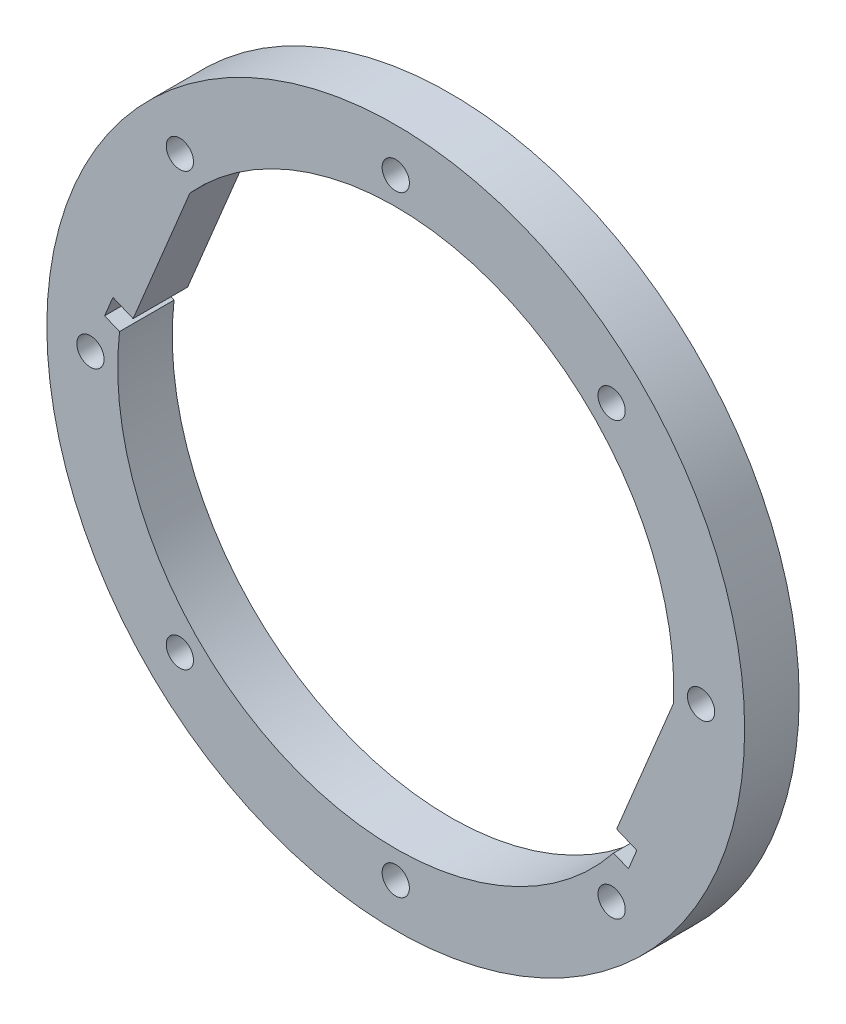
SolidWorks part; units mm, degrees
ref_plane "Alzado" through (0, 0, 0) normal (0, 0, 1) x (1, 0, 0)
ref_plane "Planta" through (0, 0, 0) normal (0, 1, 0) x (1, 0, 0)
ref_plane "Vista lateral" through (0, 0, 0) normal (1, 0, 0) x (0, 0, -1)
sketch "Croquis1" plane through (0, 0, 0) normal (0, 0, 1) x (1, 0, 0)
  circle A0 centre (0, 0) radius 32
  dimension "D1" = 64
extrude "Saliente-Extruir1" add sketch "Croquis1" along normal blind 5
sketch "Croquis2" plane through (0, 0, 5) normal (0, 0, 1) x (1, 0, 0)
  line L0 (0, 0) -> (0, 28) construction
  line L1 (0, 0) -> (19.799, 19.799) construction
  line L2 (0, 0) -> (28, 0) construction
  line L3 (0, 0) -> (19.799, -19.799) construction
  line L4 (0, 0) -> (0, -28) construction
  line L5 (0, 0) -> (-19.799, -19.799) construction
  line L6 (0, 0) -> (-28, 0) construction
  line L7 (0, 0) -> (-19.799, 19.799) construction
  circle A0 centre (0, 28) radius 1.25
  circle A1 centre (0, 0) radius 32 construction
  circle A2 centre (19.799, 19.799) radius 1.25
  circle A3 centre (28, 0) radius 1.25
  circle A4 centre (19.799, -19.799) radius 1.25
  circle A5 centre (0, -28) radius 1.25
  circle A6 centre (-19.799, -19.799) radius 1.25
  circle A7 centre (-28, 0) radius 1.25
  circle A8 centre (-19.799, 19.799) radius 1.25
  point P19 (0, 0)
  dimension "D1" = 2.5
  dimension "D2" = 28
  dimension "D3" = 8
extrude "Cortar-Extruir1" cut sketch "Croquis2" against normal through all
sketch "Croquis3" plane through (0, 0, 5) normal (0, 0, 1) x (1, 0, 0)
  line L0 (-18.8756, 17.1453) -> (-24.0865, 4.565)
  line L1 (21.3421, -16.4169) -> (-26.6997, 3.4826) construction
  line L2 (21.3421, -16.4169) -> (22.1075, -14.5692) construction
  line L3 (22.1075, -14.5692) -> (-25.9343, 5.3304) construction
  line L4 (-26.6997, 3.4826) -> (-25.9343, 5.3304) construction
  line L5 (21.3421, -16.4169) -> (-25.9343, 5.3304) construction
  line L6 (22.1075, -14.5692) -> (-26.6997, 3.4826) construction
  line L7 (-24.0865, 4.565) -> (-25.9343, 5.3304)
  line L8 (-25.9343, 5.3304) -> (-26.6997, 3.4826)
  line L9 (-26.6997, 3.4826) -> (-24.8519, 2.7172)
  line L10 (-24.8519, 2.7172) -> (-25.4706, 1.2235)
  line L11 (9.7584, 23.5589) -> (-9.7584, -23.5589) construction
  line L12 (19.4943, -15.6516) -> (18.8756, -17.1453)
  line L13 (21.3421, -16.4169) -> (19.4943, -15.6516)
  line L14 (22.1075, -14.5692) -> (21.3421, -16.4169)
  line L15 (20.2597, -13.8038) -> (22.1075, -14.5692)
  line L16 (25.4706, -1.2235) -> (20.2597, -13.8038)
  line L17 (0, 25.5) -> (0, -25.5) construction
  circle A0 centre (0, 0) radius 25.5
  point P17 (0, 0)
  point P18 (0, 0)
  dimension "D1" = 51
  dimension "D2" = 52
  dimension "D3" = 2
  dimension "D4" = 2
  dimension "D5" = 22.5
  dimension "D6" = 5
extrude "Cortar-Extruir2" cut sketch "Croquis3" against normal blind 10 contours L16 A0 L0 L7 L8 L9 L10 L12 L13 L14 L15 | A0 L7 L8 L9 | A0 L13 L14 L15 | L12 A0 L13 | L9 A0 L10
